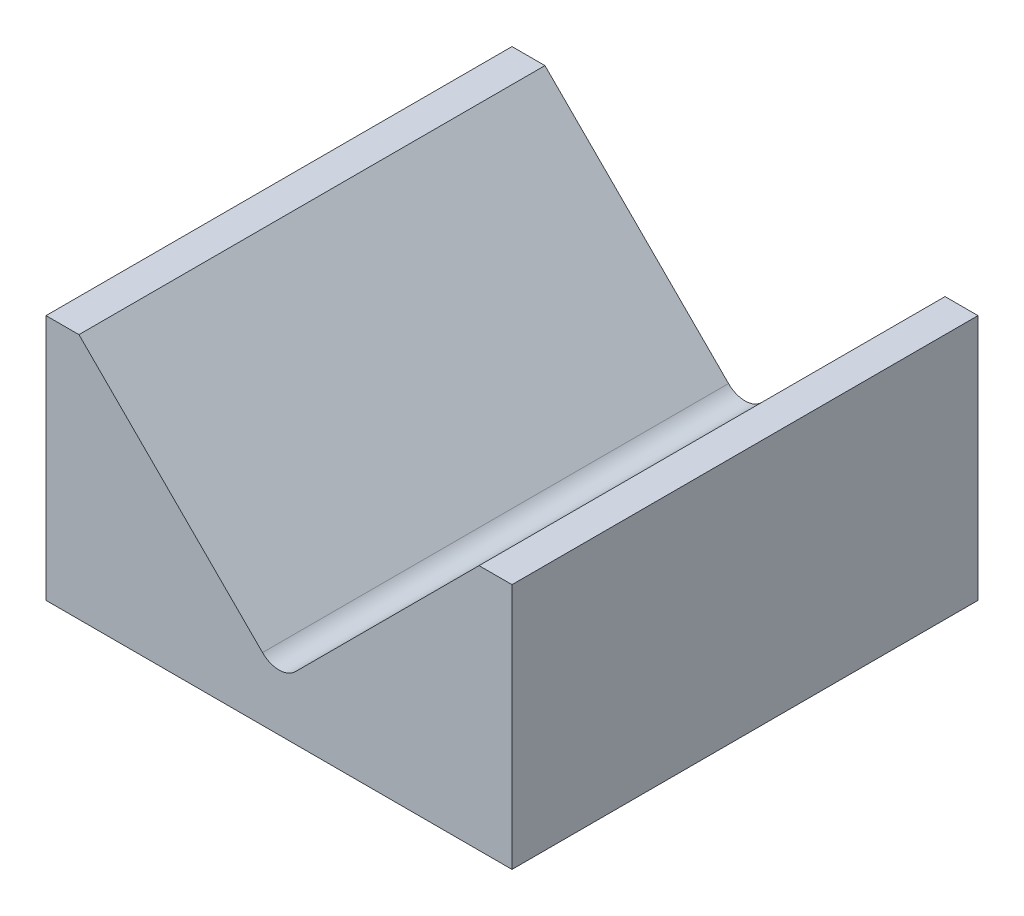
SolidWorks part; units mm, degrees
ref_plane "前视基准面" through (0, 0, 0) normal (0, 0, 1) x (1, 0, 0)
ref_plane "上视基准面" through (0, 0, 0) normal (0, 1, 0) x (1, 0, 0)
ref_plane "右视基准面" through (0, 0, 0) normal (1, 0, 0) x (0, 0, -1)
sketch "草图2" plane through (0, 0, 0) normal (0, 0, 1) x (1, 0, 0)
  line L0 (0, 0) -> (0, 6)
  line L1 (0, 6) -> (5, 1)
  line L2 (5, 1) -> (10, 6)
  line L3 (10, 6) -> (10, 0)
  line L4 (10, 0) -> (0, 0)
  dimension "D1" = 10
  dimension "D2" = 6
  dimension "D3" = 5
  dimension "D4" = 5
extrude "凸台-拉伸1" add sketch "草图2" along normal blind 10
fillet "圆角1" radius 0.5 1 edges at (5, 1, 5)
chamfer "倒角1" distance 1 angle 45 2 edges at (0, 6, 5) (10, 6, 5)
